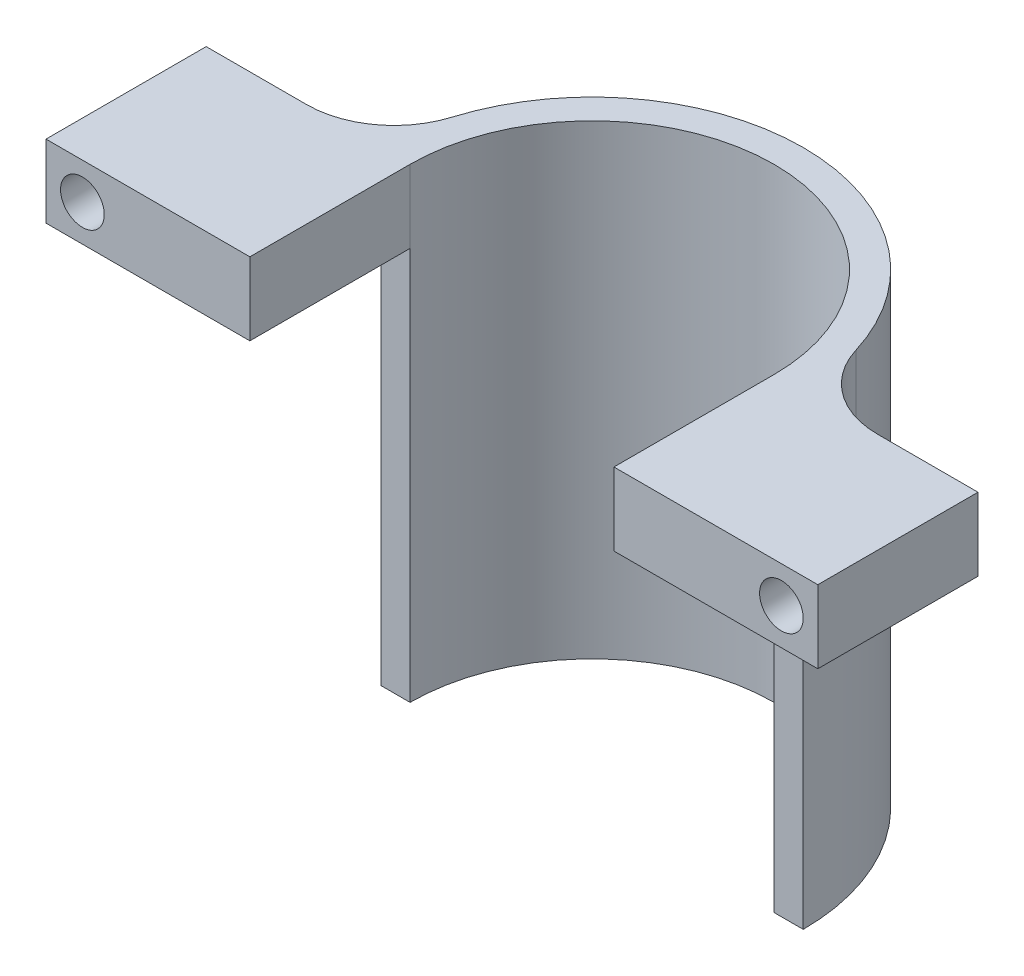
SolidWorks part; units mm, degrees
ref_plane "Front Plane" through (0, 0, 0) normal (0, 0, 1) x (1, 0, 0)
ref_plane "Top Plane" through (0, 0, 0) normal (0, 1, 0) x (1, 0, 0)
ref_plane "Right Plane" through (0, 0, 0) normal (1, 0, 0) x (0, 0, -1)
sketch "Sketch1" plane through (0, 0, 0) normal (0, 1, 0) x (1, 0, 0)
  line L0 (-14.5, 0) -> (-12.5, 0)
  line L1 (12.5, 0) -> (14.5, 0)
  arc A0 (12.5, 0) -> (-12.5, 0) centre (0, 0) ccw
  arc A1 (14.5, 0) -> (-14.5, 0) centre (0, 0) ccw
  dimension "D1" = 25
  dimension "D2" = 29
extrude "Boss-Extrude1" add sketch "Sketch1" along normal blind 32
sketch "Sketch2" plane through (0, 0, 0) normal (0, 0, 1) x (1, 0, 0)
  line L0 (-12.5, 32) -> (-12.5, 0) construction
  line L1 (-14.5, 32) -> (-12.5, 32)
  line L3 (-14.5, 27) -> (-12.5, 27)
  line L4 (-12.5, 32) -> (-12.5, 27)
  line L5 (0, 0) -> (0, 32) construction
  line L6 (12.5, 32) -> (-12.5, 32) construction
  line L7 (12.5, 32) -> (12.5, 27)
  line L8 (14.5, 27) -> (12.5, 27)
  line L10 (14.5, 32) -> (12.5, 32)
  line L11 (14.5, 32) -> (26.5, 32)
  line L12 (-14.5, 32) -> (-26.5, 32)
  line L14 (-14.5, 27) -> (-26.5, 27)
  line L15 (-26.5, 32) -> (-26.5, 27)
  line L16 (14.5, 27) -> (26.5, 27)
  line L17 (26.5, 32) -> (26.5, 27)
  dimension "D1" = 5
  dimension "D2" = 12
  dimension "D3" = 5
extrude "Boss-Extrude2" add sketch "Sketch2" along normal blind 11
sketch "Sketch3" plane through (0, 0, 0) normal (0, 0, -1) x (-1, 0, 0)
  line L0 (26.5, 27) -> (14.5, 27) construction
  line L1 (26.5, 32) -> (26.5, 27) construction
  line L2 (0, 0) -> (0, 32) construction
  line L3 (14.5, 32) -> (-14.5, 32) construction
  circle A0 centre (24, 29.5) radius 1.5
  circle A1 centre (-24, 29.5) radius 1.5
  dimension "D1" = 3
  dimension "D2" = 2.5
  dimension "D3" = 2.5
extrude "Cut-Extrude1" cut sketch "Sketch3" against normal through all
fillet "Fillet1" radius 6 2 edges at (14.5, 29.5, 0) (-14.5, 29.5, 0)
